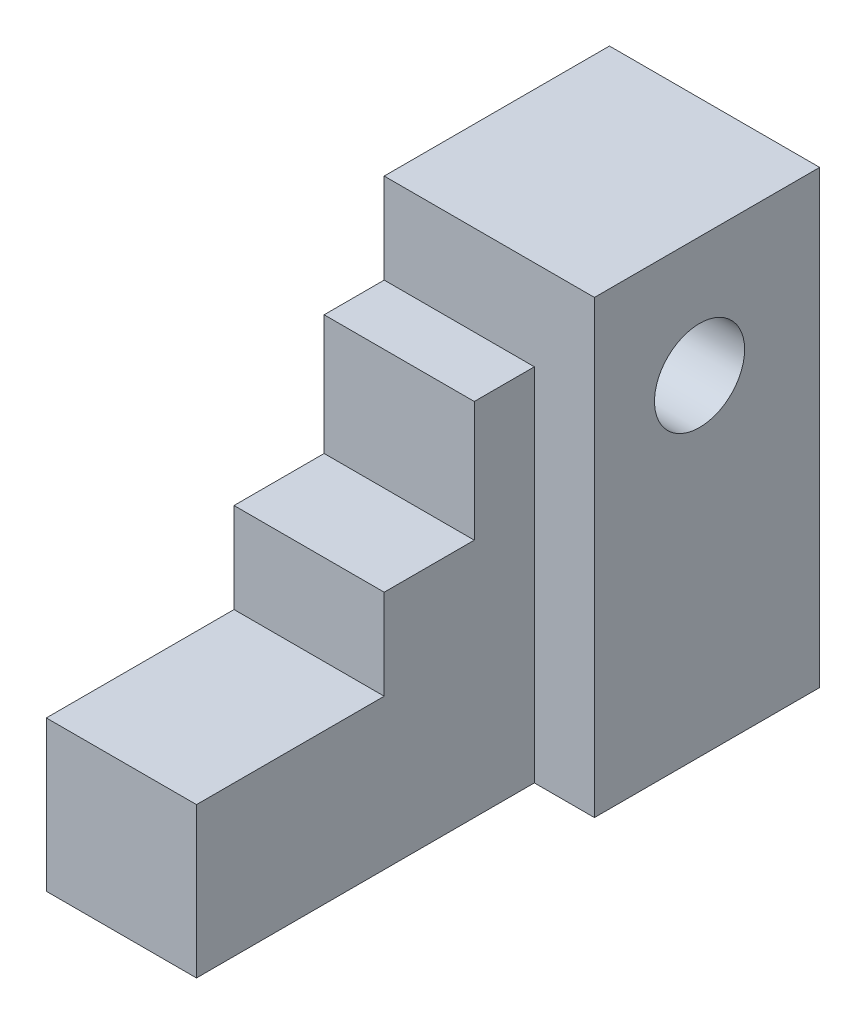
SolidWorks part; units mm, degrees
ref_plane "Front Plane" through (0, 0, 0) normal (1, 0, 0) x (0, 1, 0)
ref_plane "Top Plane" through (0, 0, 0) normal (0, 0, 1) x (0, 1, 0)
ref_plane "Right Plane" through (0, 0, 0) normal (0, 1, 0) x (-1, 0, 0)
sketch "Sketch2" plane through (0, 0, 0) normal (1, 0, 0) x (0, 1, 0)
  line L0 (0, 0) -> (60, 0)
  line L2 (0, 75) -> (0, 0)
  line L3 (0, 75) -> (20, 75)
  line L4 (20, 75) -> (20, 50)
  line L5 (20, 50) -> (32, 50)
  line L6 (32, 50) -> (32, 38)
  line L7 (32, 38) -> (48, 38)
  line L8 (48, 38) -> (48, 30)
  line L9 (48, 30) -> (60, 30)
  line L10 (60, 30) -> (60, 0)
  dimension "D1" = 75
  dimension "D2" = 60
  dimension "D3" = 20
  dimension "D4" = 12
  dimension "D5" = 12
  dimension "D6" = 12
  dimension "D7" = 8
  dimension "D8" = 30
extrude "Boss-Extrude2" add sketch "Sketch2" along normal blind 28
sketch "Sketch3" plane through (0, 0, 0) normal (1, 0, 0) x (0, 1, 0)
  line L0 (48, 30) -> (0, 30)
  line L1 (0, 75) -> (0, 0) construction
  line L2 (0, 30) -> (0, 75)
  line L3 (0, 75) -> (20, 75)
  line L4 (20, 75) -> (20, 50)
  line L5 (20, 50) -> (32, 50)
  line L6 (32, 50) -> (32, 38)
  line L7 (32, 38) -> (48, 38)
  line L8 (48, 38) -> (48, 30)
extrude "Cut-Extrude2" cut sketch "Sketch3" against normal blind 8 from surface at 28 starting at face at (28, 32, 38.6)
sketch "Sketch4" plane through (0, 0, 0) normal (1, 0, 0) x (0, 1, 0)
  line L0 (60, 0) -> (60, 30) construction
  line L1 (0, 0) -> (60, 0) construction
  circle A0 centre (44, 16) radius 6
  dimension "D1" = 12
  dimension "D2" = 16
  dimension "D3" = 16
extrude "Cut-Extrude3" cut sketch "Sketch4" along normal blind 28
